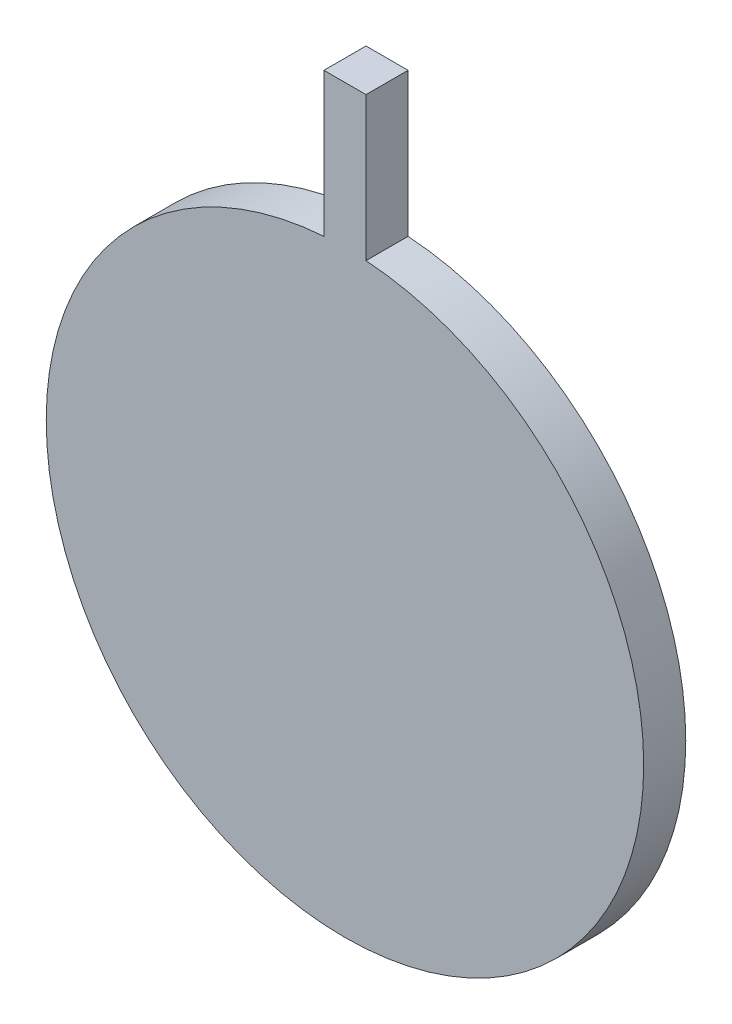
SolidWorks part; units mm, degrees
ref_plane "Front Plane" through (0, 0, 0) normal (0, 0, 1) x (1, 0, 0)
ref_plane "Top Plane" through (0, 0, 0) normal (0, 1, 0) x (1, 0, 0)
ref_plane "Right Plane" through (0, 0, 0) normal (1, 0, 0) x (0, 0, -1)
sketch "Sketch1" plane through (0, 0, 0) normal (0, 0, 1) x (1, 0, 0)
  circle A0 centre (0, 0) radius 18.034
  dimension "D1" = 36.068
extrude "Boss-Extrude1" add sketch "Sketch1" along normal blind 2.54
ref_plane "Plane1" through (0, 17.78, 0) normal (0, 1, 0) x (1, 0, 0)
sketch "Sketch2" plane through (0, 17.78, 0) normal (0, 1, 0) x (1, 0, 0)
  line L0 (18.034, 0) -> (-18.034, 0) construction
  line L1 (1.27, -2.54) -> (-1.27, -2.54)
  line L2 (1.27, -2.54) -> (1.27, 0)
  line L3 (1.27, 0) -> (-1.27, 0)
  line L4 (-1.27, -2.54) -> (-1.27, 0)
  line L5 (1.27, -2.54) -> (-1.27, 0) construction
  line L6 (1.27, 0) -> (-1.27, -2.54) construction
  point P0 (0, -1.27)
  point P5 (1.2184, -1.4133)
  point P9 (0, -1.27)
  point P10 (0, 0)
  dimension "D1" = 1.27
  dimension "D2" = 2.54
extrude "Boss-Extrude2" add sketch "Sketch2" along normal blind 8.89 separate body
combine bodies "Combine1" operation type add bodies to combine 101 102
